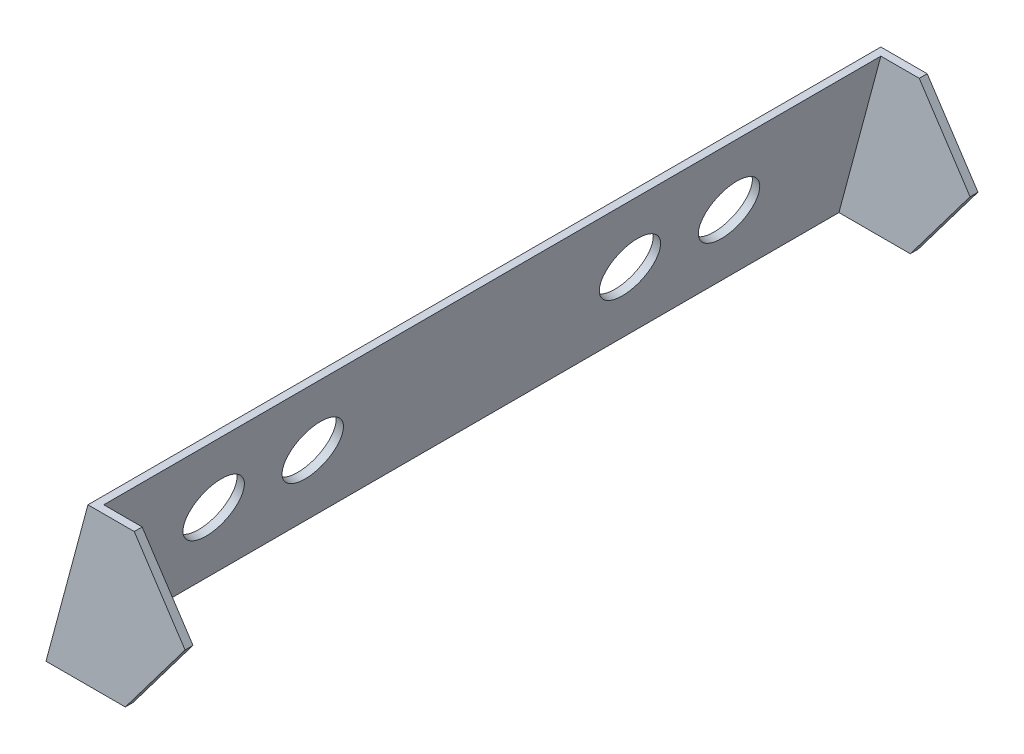
SolidWorks part; units mm, degrees
ref_plane "Front Plane" through (0, 0, 0) normal (0, 0, 1) x (1, 0, 0)
ref_plane "Top Plane" through (0, 0, 0) normal (0, 1, 0) x (1, 0, 0)
ref_plane "Right Plane" through (0, 0, 0) normal (1, 0, 0) x (0, 0, -1)
sketch "Sketch1" plane through (0, 0, 0) normal (0, 0, 1) x (1, 0, 0)
  line L2 (10.5742, 19.4635) -> (22.2565, 19.4635)
  line L3 (22.2565, 19.4635) -> (35.0761, 0)
  line L4 (0, -20) -> (20, -20)
  line L5 (20, -20) -> (35.0761, 0)
  line L6 (0, -20) -> (10.5742, 19.4635)
extrude "Boss-Extrude1" add sketch "Sketch1" along normal blind 2 contours L2 L3 L5 L4 L6
sketch "Sketch2" plane through (0, 0, 2) normal (0, 0, 1) x (1, 0, 0)
  line L0 (10.5742, 19.4635) -> (12.5742, 19.4635)
  line L1 (10.5742, 19.4635) -> (22.2565, 19.4635) construction
  line L2 (12.5742, 19.4635) -> (2, -20)
  line L3 (0, -20) -> (20, -20) construction
  line L4 (2, -20) -> (0, -20)
  line L5 (0, -20) -> (10.5742, 19.4635)
extrude "Boss-Extrude2" add sketch "Sketch2" against normal blind 200
ref_plane "Plane1" through (0, 0, -98) normal (0, 0, 1) x (1, 0, 0)
mirror "Mirror1" about plane through (0, 0, -98) normal (0, 0, 1) of "Boss-Extrude1"
sketch "Sketch3" plane through (6.866, -1.8397, 0) normal (0.9659, -0.2588, 0) x (0, 0, -1)
  circle A0 centre (58, 1.6269) radius 7.5
  circle A1 centre (33, 1.6269) radius 7.5
  circle A2 centre (163, 1.6269) radius 7.5
  circle A3 centre (138, 1.6269) radius 7.5
  dimension "D1" = 2
extrude "Cut-Extrude1" cut sketch "Sketch3" against normal blind 200
